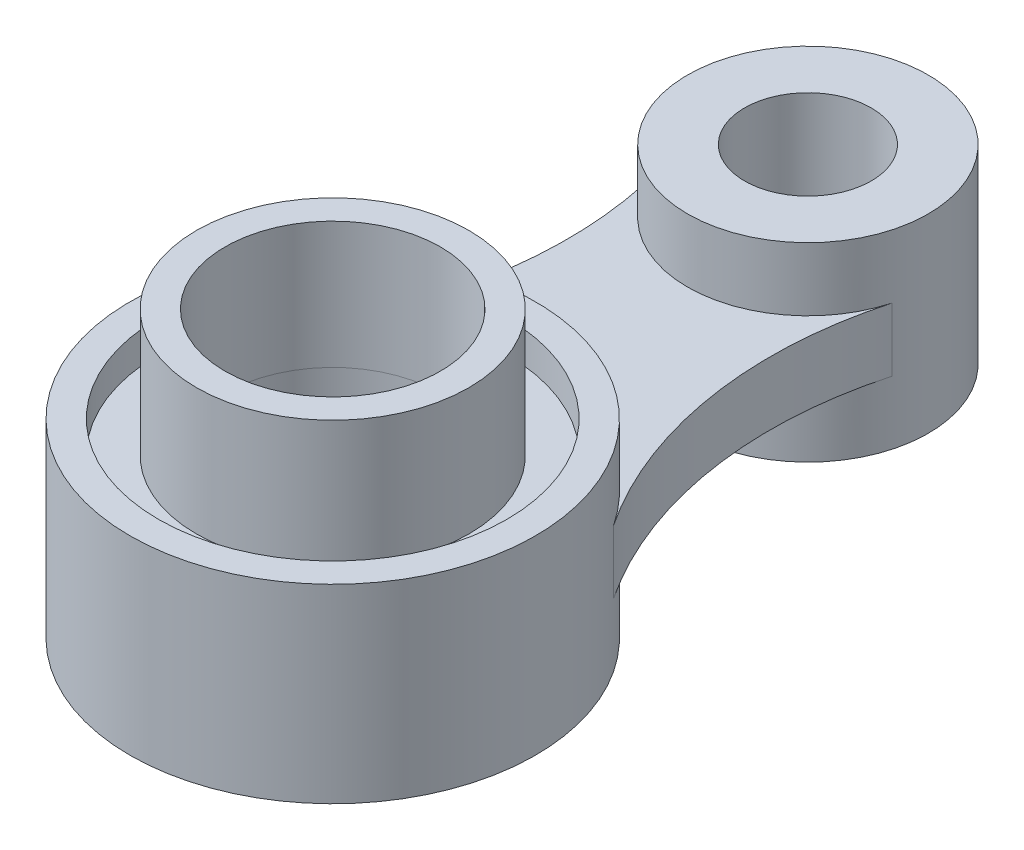
SolidWorks part; units mm, degrees
ref_plane "Front Plane" through (0, 0, 0) normal (0, 0, 1) x (1, 0, 0)
ref_plane "Top Plane" through (0, 0, 0) normal (0, 1, 0) x (1, 0, 0)
ref_plane "Right Plane" through (0, 0, 0) normal (1, 0, 0) x (0, 0, -1)
sketch "Sketch1" plane through (0, 0, 0) normal (0, 1, 0) x (1, 0, 0)
  line L0 (0, 37.5) -> (0, -37.5) construction
  point P4 (0, 0)
  point P8 (0, 0)
  dimension "D1" = 75
sketch "Sketch2" plane through (0, 0, 0) normal (0, 1, 0) x (1, 0, 0)
  circle A0 centre (0, 37.5) radius 19
  circle A1 centre (0, -37.5) radius 32
  dimension "D1" = 38
  dimension "D2" = 64
extrude "Boss-Extrude1" add sketch "Sketch2" along normal blind 30
ref_plane "Plane1" through (0, 10, 0) normal (0, 1, 0) x (1, 0, 0)
sketch "Sketch3" plane through (0, 10, 0) normal (0, 1, 0) x (1, 0, 0)
  circle A0 centre (0, 37.5) radius 19 construction
  arc A1 (-18.3212, 32.4669) -> (18.3212, 32.4669) centre (0, 37.5) ccw
  circle A2 centre (0, -37.5) radius 32 construction
  arc A3 (26.6783, -19.8289) -> (-26.6783, -19.8289) centre (0, -37.5) ccw
  arc A4 (-18.3212, 32.4669) -> (-26.6783, -19.8289) centre (-80.0349, 15.5133) cw
  arc A5 (18.3212, 32.4669) -> (26.6783, -19.8289) centre (80.0349, 15.5133) ccw
  dimension "D1" = 64
extrude "Boss-Extrude2" add sketch "Sketch3" along normal blind 10
ref_plane "Plane2" through (0, 25, 0) normal (0, 1, 0) x (1, 0, 0)
sketch "Sketch4" plane through (0, 25, 0) normal (0, 1, 0) x (1, 0, 0)
  circle A0 centre (0, -37.5) radius 27.5
  dimension "D1" = 55
extrude "Cut-Extrude1" cut sketch "Sketch4" along normal blind 5
sketch "Sketch5" plane through (0, 25, 0) normal (0, 1, 0) x (1, 0, 0)
  circle A0 centre (0, -37.5) radius 21.5
  dimension "D1" = 43
extrude "Boss-Extrude3" add sketch "Sketch5" along normal blind 20 separate body
sketch "Sketch6" plane through (0, 0, 0) normal (0, 1, 0) x (1, 0, 0)
  circle A0 centre (0, 37.5) radius 10
  circle A1 centre (0, -37.5) radius 17
  dimension "D1" = 34
  dimension "D2" = 20
extrude "Cut-Extrude3" cut sketch "Sketch6" along normal through all both and the other way through all
